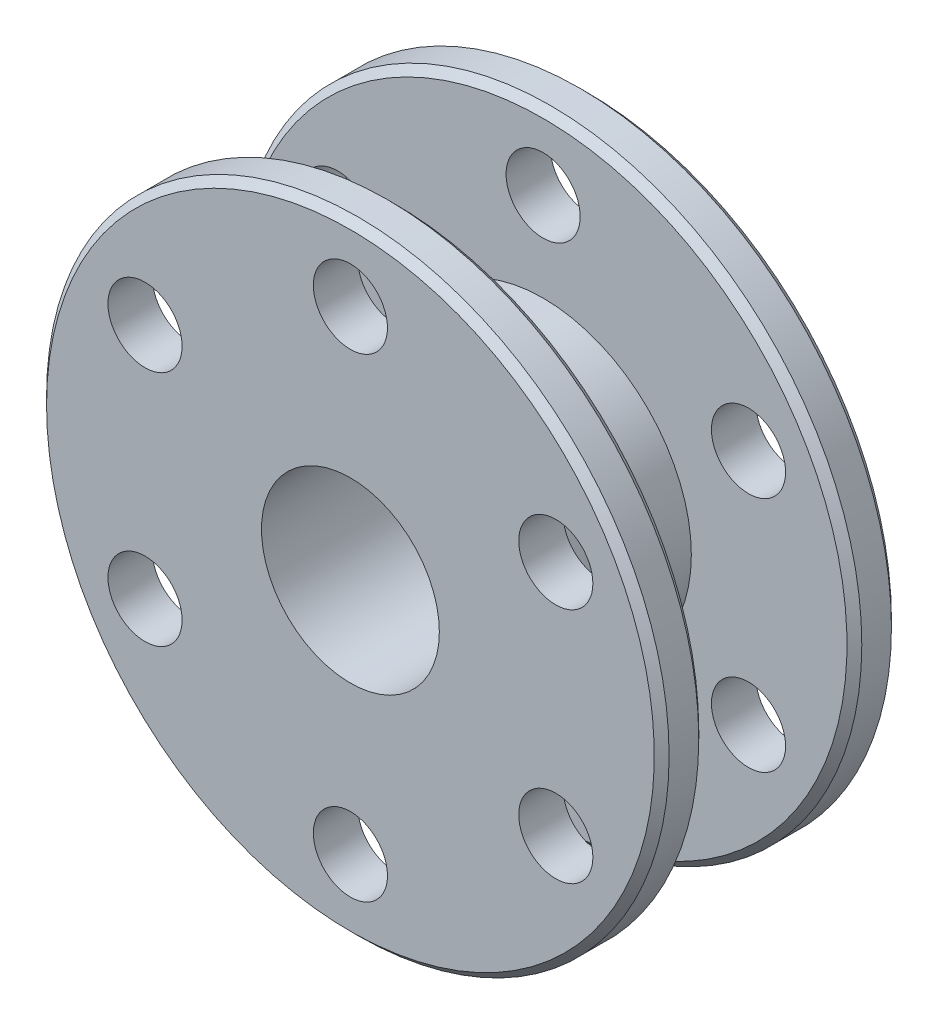
SolidWorks part; units mm, degrees
ref_plane "Front Plane" through (0, 0, 0) normal (0, 0, 1) x (1, 0, 0)
ref_plane "Top Plane" through (0, 0, 0) normal (0, 1, 0) x (1, 0, 0)
ref_plane "Right Plane" through (0, 0, 0) normal (1, 0, 0) x (0, 0, -1)
sketch "Sketch1" plane through (0, 0, 0) normal (1, 0, 0) x (0, 0, -1)
  line L0 (-24.7907, 0) -> (19.9333, 0) construction
  line L1 (-13.2486, 6) -> (-13.2486, 21)
  line L2 (-13.2486, 21) -> (-10.2486, 21)
  line L3 (-10.2486, 21) -> (-10.2486, 10)
  line L4 (-10.2486, 10) -> (-0.2486, 10)
  line L5 (-0.2486, 10) -> (-0.2486, 21)
  line L6 (-0.2486, 21) -> (2.7514, 21)
  line L7 (2.7514, 21) -> (2.7514, 6)
  line L8 (2.7514, 6) -> (-13.2486, 6)
  dimension "D1" = 16
  dimension "D2" = 6
  dimension "D3" = 21
  dimension "D4" = 10
  dimension "D5" = 3
  dimension "D6" = 3
revolve "Revolve1" add sketch "Sketch1" angle 360 about L0
chamfer "Chamfer1" distance 0.5 angle 45 4 edges at (21, 0, -2.7514) (21, 0, 0.2486) (21, 0, 10.2486) (21, 0, 13.2486)
sketch "Sketch2" plane through (0, 0, 13.2486) normal (0, 0, 1) x (1, 0, 0)
  line L0 (0, 16) -> (0, 0) construction
  circle A0 centre (0, 16) radius 2.5
  circle A1 centre (13.8564, 8) radius 2.5
  circle A2 centre (13.8564, -8) radius 2.5
  circle A3 centre (0, -16) radius 2.5
  circle A4 centre (-13.8564, -8) radius 2.5
  circle A5 centre (-13.8564, 8) radius 2.5
  point P17 (0, 0)
  dimension "D1" = 5
  dimension "D2" = 16
  dimension "D3" = 6
extrude "Cut-Extrude1" cut sketch "Sketch2" against normal through all both and the other way through all
